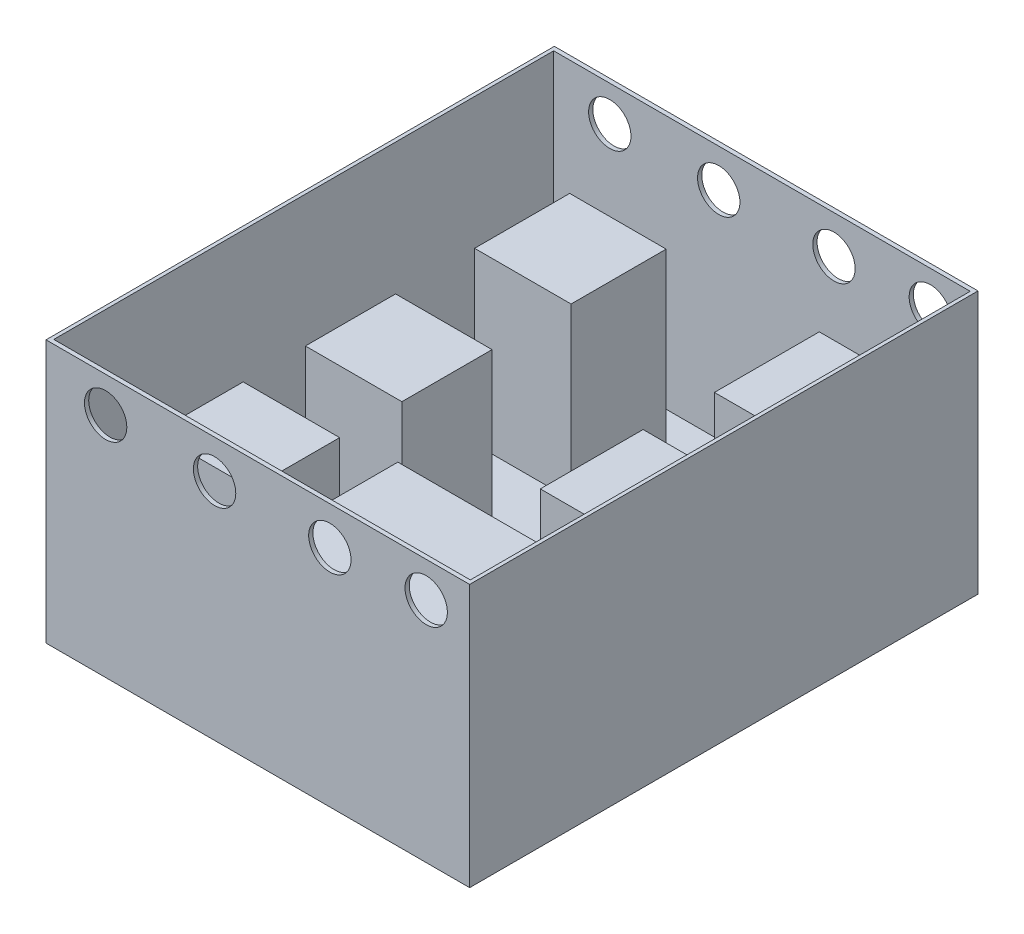
SolidWorks part; units mm, degrees
ref_plane "Front Plane" through (0, 0, 0) normal (0, 0, 1) x (1, 0, 0)
ref_plane "Top Plane" through (0, 0, 0) normal (0, 1, 0) x (1, 0, 0)
ref_plane "Right Plane" through (0, 0, 0) normal (1, 0, 0) x (0, 0, -1)
sketch "Sketch1" plane through (0, 0, 0) normal (0, 1, 0) x (1, 0, 0)
  line L1 (-500, 600) -> (500, 600)
  line L2 (-500, 600) -> (-500, -600)
  line L3 (-500, -600) -> (500, -600)
  line L4 (500, 600) -> (500, -600)
  line L5 (-500, 600) -> (500, -600) construction
  line L6 (-500, -600) -> (500, 600) construction
  point P0 (0, 0)
  dimension "D1" = 1200
  dimension "D2" = 1000
extrude "Boss-Extrude1" add sketch "Sketch1" along normal blind 20
sketch "Sketch2" plane through (0, 20, 0) normal (0, 1, 0) x (1, 0, 0)
  line L1 (-500, 600) -> (500, 600)
  line L2 (-500, 600) -> (-500, -600)
  line L3 (-500, -600) -> (500, -600)
  line L4 (500, 600) -> (500, -600)
  line L5 (-500, 600) -> (500, -600) construction
  line L6 (-500, -600) -> (500, 600) construction
  line L7 (-491.6667, 590) -> (491.6667, 590)
  line L8 (-491.6667, 590) -> (-491.6667, -590)
  line L9 (-491.6667, -590) -> (491.6667, -590)
  line L10 (491.6667, 590) -> (491.6667, -590)
  line L11 (-491.6667, 590) -> (491.6667, -590) construction
  line L12 (-491.6667, -590) -> (491.6667, 590) construction
  point P0 (0, 0)
  point P7 (0, 0)
  dimension "D1" = 1180
extrude "Boss-Extrude2" add sketch "Sketch2" along normal blind 600
sketch "Sketch3" plane through (0, 20, 0) normal (0, 1, 0) x (1, 0, 0)
  line L1 (-381.236, 517.3918) -> (-153.4846, 517.3918)
  line L2 (-381.236, 517.3918) -> (-381.236, 292.9411)
  line L3 (-381.236, 292.9411) -> (-153.4846, 292.9411)
  line L4 (-153.4846, 517.3918) -> (-153.4846, 292.9411)
  line L5 (-381.236, 517.3918) -> (-153.4846, 292.9411) construction
  line L6 (-381.236, 292.9411) -> (-153.4846, 517.3918) construction
  line L7 (196.3943, 528.9444) -> (424.1457, 528.9444)
  line L8 (196.3943, 528.9444) -> (196.3943, 281.3885)
  line L9 (196.3943, 281.3885) -> (424.1457, 281.3885)
  line L10 (424.1457, 528.9444) -> (424.1457, 281.3885)
  line L11 (196.3943, 528.9444) -> (424.1457, 281.3885) construction
  line L12 (196.3943, 281.3885) -> (424.1457, 528.9444) construction
  line L13 (-381.236, 106.449) -> (-153.4846, 106.449)
  line L14 (-381.236, 106.449) -> (-381.236, -106.449)
  line L15 (-381.236, -106.449) -> (-153.4846, -106.449)
  line L16 (-153.4846, 106.449) -> (-153.4846, -106.449)
  line L17 (-381.236, 106.449) -> (-153.4846, -106.449) construction
  line L18 (-381.236, -106.449) -> (-153.4846, 106.449) construction
  line L19 (188.1425, 121.3024) -> (432.3976, 121.3024)
  line L20 (188.1425, 121.3024) -> (188.1425, -121.3024)
  line L21 (188.1425, -121.3024) -> (432.3976, -121.3024)
  line L22 (432.3976, 121.3024) -> (432.3976, -121.3024)
  line L23 (188.1425, 121.3024) -> (432.3976, -121.3024) construction
  line L24 (188.1425, -121.3024) -> (432.3976, 121.3024) construction
  line L25 (-381.236, -253.3322) -> (-153.4846, -253.3322)
  line L26 (-381.236, -253.3322) -> (-381.236, -461.2791)
  line L27 (-381.236, -461.2791) -> (-153.4846, -461.2791)
  line L28 (-153.4846, -253.3322) -> (-153.4846, -461.2791)
  line L29 (-381.236, -253.3322) -> (-153.4846, -461.2791) construction
  line L30 (-381.236, -461.2791) -> (-153.4846, -253.3322) construction
  line L31 (-34.6578, -234.7898) -> (453.8524, -234.7898)
  line L32 (-34.6578, -234.7898) -> (-34.6578, -555.7387)
  line L33 (-34.6578, -555.7387) -> (453.8524, -555.7387)
  line L34 (453.8524, -234.7898) -> (453.8524, -555.7387)
  line L35 (-34.6578, -234.7898) -> (453.8524, -555.7387) construction
  line L36 (-34.6578, -555.7387) -> (453.8524, -234.7898) construction
  point P0 (-267.3603, 405.1664)
  point P5 (310.27, 405.1664)
  point P10 (-267.3603, 0)
  point P15 (310.27, 0)
  point P20 (-267.3603, -357.3056)
  point P25 (209.5973, -395.2642)
  point P30 (310.27, 0)
  point P31 (310.27, 405.1664)
  point P32 (-267.3603, 405.1664)
  point P33 (-267.3603, 0)
  point P34 (-267.3603, -357.3056)
extrude "Boss-Extrude3" add sketch "Sketch3" along normal blind 400
sketch "Sketch5" plane through (0, 420, 0) normal (0, 1, 0) x (1, 0, 0)
  text T0 "LAUNCH COMMAND\r\nCIRCUIT\r\n" font "Century Gothic" height 17
sketch "Sketch6" plane through (0, 420, 0) normal (0, 1, 0) x (1, 0, 0)
  text T0 "FUELLING COMMAND\r\nCIRCUIT" font "Century Gothic" height 16
sketch "Sketch7" plane through (0, 420, 0) normal (0, 1, 0) x (1, 0, 0)
  text T0 "LINEAR ACTUATOR\r\nCONTROL" font "Century Gothic" height 16
sketch "Sketch10" plane through (0, 420, 0) normal (0, 1, 0) x (1, 0, 0)
  text T0 "WHEELED RAIL\r\nMOTOR CONTROL" font "Century Gothic" height 16
sketch "Sketch11" plane through (0, 420, 0) normal (0, 1, 0) x (1, 0, 0)
  text T0 "IGNITOR\r\nCIRCUIT" font "Century Gothic" height 25
sketch "Sketch12" plane through (0, 420, 0) normal (0, 1, 0) x (1, 0, 0)
  text T0 "SENSORS AND\r\nDATA COLLECTOR" font "Century Gothic" height 22
sketch "Sketch13" plane through (0, 0, 600) normal (0, 0, 1) x (1, 0, 0)
  circle A0 centre (-359.2061, 536.5649) radius 50
  circle A1 centre (-102.023, 530.1884) radius 50
  circle A2 centre (170.0384, 530.1884) radius 50
  circle A3 centre (397.4647, 536.5649) radius 50
  dimension "D1" = 100
  dimension "D2" = 100
  dimension "D3" = 100
  dimension "D4" = 100
extrude "Cut-Extrude1" cut sketch "Sketch13" against normal through all
